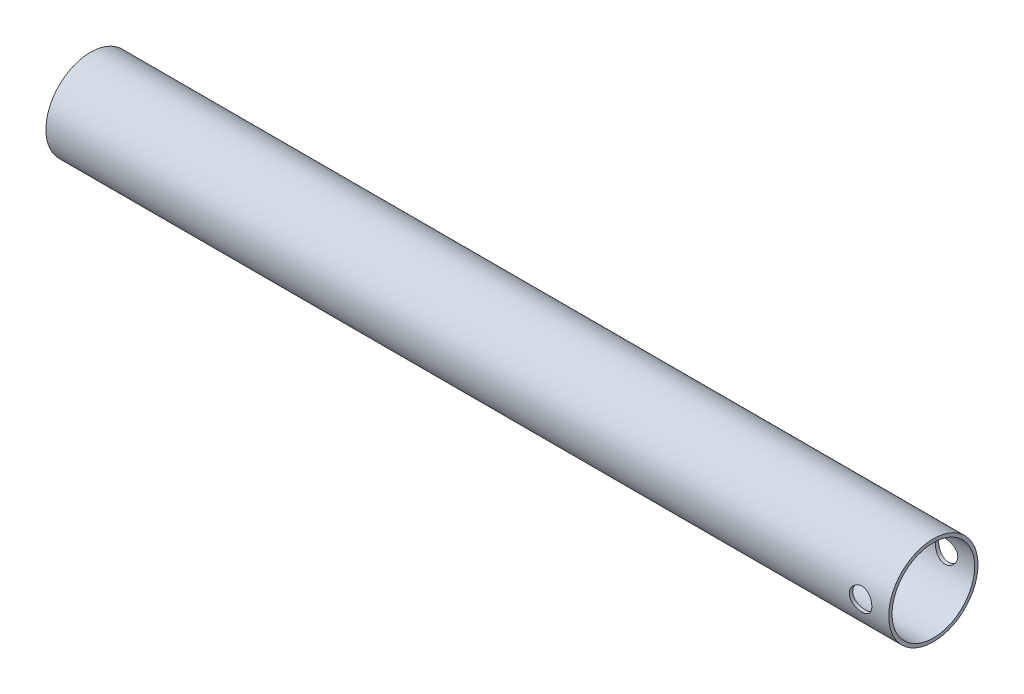
SolidWorks part; units mm, degrees
ref_plane "Front Plane" through (0, 0, 0) normal (0, 0, 1) x (1, 0, 0)
ref_plane "Top Plane" through (0, 0, 0) normal (0, 1, 0) x (1, 0, 0)
ref_plane "Right Plane" through (0, 0, 0) normal (1, 0, 0) x (0, 0, -1)
sketch "Sketch1" plane through (0, 0, 0) normal (1, 0, 0) x (0, 0, -1)
  circle A0 centre (0, 0) radius 14.7
  circle A1 centre (0, 0) radius 15.9
  dimension "D1" = 31.8
  dimension "D2" = 1.2
extrude "Boss-Extrude1" add sketch "Sketch1" along normal blind 300
sketch "Sketch3" plane through (300, 0, 0) normal (1, 0, 0) x (0, 0, -1)
  line L0 (14.7, 0) -> (15.9, 0)
  circle A0 centre (0, 0) radius 14.7 construction
  circle A1 centre (0, 0) radius 15.9 construction
ref_plane "Plane1" through (0, 0, -15.9) normal (0, 0, -1) x (-1, 0, 0)
sketch "Sketch4" plane through (0, 0, -15.9) normal (0, 0, -1) x (1, 0, 0)
  line L2 (300, -15.9) -> (300, 15.9) construction
  circle A0 centre (290, 0) radius 4
  dimension "D3" = 8
  dimension "D1" = 10
  dimension "D2" = 0
extrude "Cut-Extrude1" cut sketch "Sketch4" against normal through all contours A0
